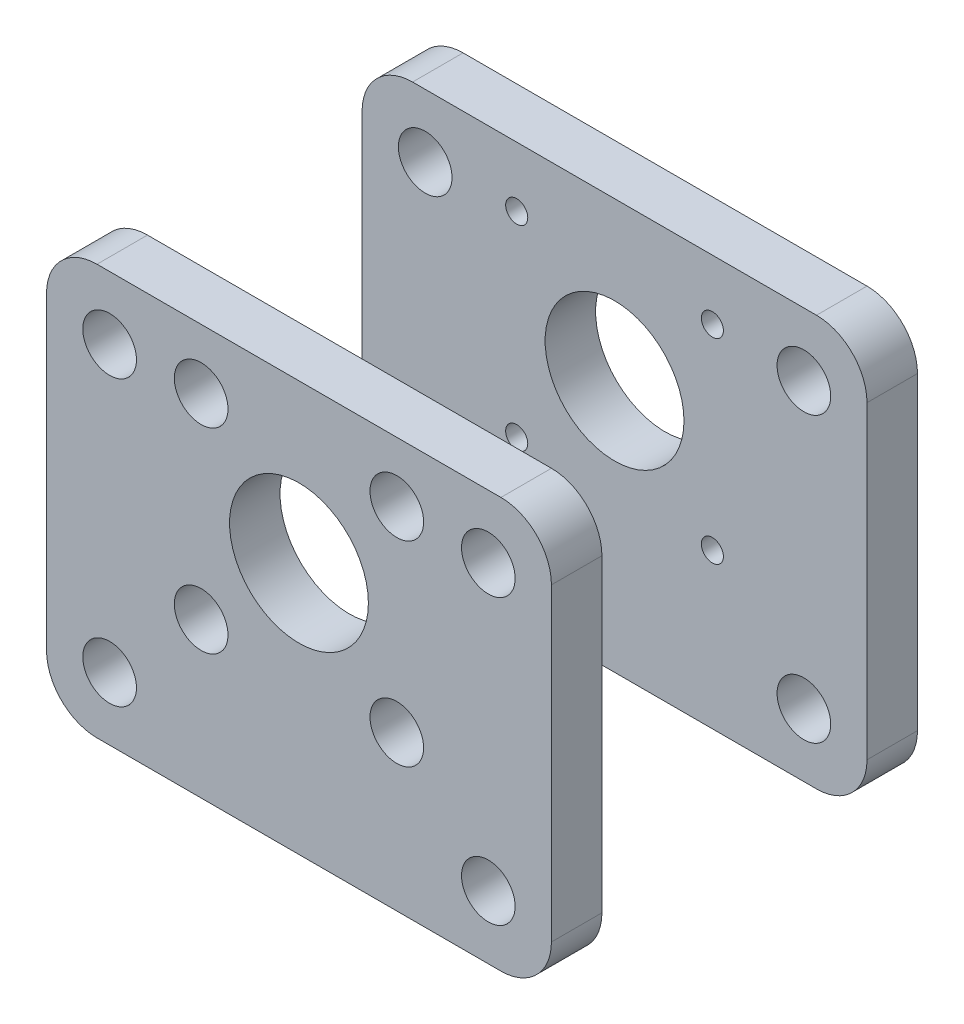
SolidWorks part; units mm, degrees
material "PET"
ref_plane "xy-antrieb" through (0, 0, 0) normal (0, 0, 1) x (1, 0, 0)
ref_plane "xz" through (0, 0, 0) normal (0, 1, 0) x (1, 0, 0)
ref_plane "yz" through (0, 0, 0) normal (1, 0, 0) x (0, 0, -1)
sketch "Skizze1" plane through (0, 0, 0) normal (0, 0, 1) x (1, 0, 0)
  line L1 (-40, 25) -> (40, 25)
  line L2 (-40, 25) -> (-40, -40)
  line L3 (-40, -40) -> (40, -40)
  line L4 (40, 25) -> (40, -40)
  line L5 (-15.5, 15.5) -> (15.5, 15.5) construction
  line L6 (-15.5, 15.5) -> (-15.5, -15.5) construction
  line L7 (-15.5, -15.5) -> (15.5, -15.5) construction
  line L8 (15.5, 15.5) -> (15.5, -15.5) construction
  line L9 (-30, 15) -> (30, 15) construction
  line L10 (-30, 15) -> (-30, -30) construction
  line L11 (-30, -30) -> (30, -30) construction
  line L12 (30, 15) -> (30, -30) construction
  circle A0 centre (0, 0) radius 11
  circle A1 centre (-15.5, 15.5) radius 1.75
  circle A2 centre (-15.5, -15.5) radius 1.75
  circle A3 centre (15.5, 15.5) radius 1.75
  circle A4 centre (15.5, -15.5) radius 1.75
  circle A5 centre (-30, 15) radius 10 construction
  circle A6 centre (-30, 15) radius 4.25
  circle A7 centre (30, 15) radius 4.25
  circle A8 centre (-30, -30) radius 4.25
  circle A9 centre (30, -30) radius 4.25
  point P4 (0, -40)
  point P12 (0, 15.5)
  point P13 (-15.5, 0)
  point P26 (0, -30)
  dimension "D1" = 22
  dimension "D3" = 3.5
  dimension "D4" = 10
  dimension "D5" = 8.5
  dimension "D6" = 80
  dimension "D8" = 10
  dimension "D2" = 31
  dimension "D7" = 30
  dimension "D9" = 65
extrude "Aufsatz-Linear austragen1" add sketch "Skizze1" along normal mid plane 8
ref_plane "xy-lager-mitte" through (0, 0, 50) normal (0, 0, 1) x (1, 0, 0)
sketch "Skizze2" plane through (0, 0, 50) normal (0, 0, 1) x (1, 0, 0)
  line L1 (-40, 25) -> (40, 25)
  line L2 (-40, 25) -> (-40, -40)
  line L3 (-40, -40) -> (40, -40)
  line L4 (40, 25) -> (40, -40)
  circle A0 centre (0, 0) radius 11
  circle A1 centre (-30, 15) radius 4.25 construction
  circle A2 centre (-30, 15) radius 4.25
  circle A3 centre (-30, -30) radius 4.25 construction
  circle A4 centre (-30, -30) radius 4.25
  circle A5 centre (30, -30) radius 4.25 construction
  circle A6 centre (30, -30) radius 4.25
  circle A7 centre (30, 15) radius 4.25 construction
  circle A8 centre (30, 15) radius 4.25
  circle A9 centre (-15.5, 15.5) radius 4.25
  circle A10 centre (-15.5, -15.5) radius 4.25
  circle A11 centre (15.5, -15.5) radius 4.25
  circle A12 centre (15.5, 15.5) radius 4.25
  dimension "D1" = 22
  dimension "D2" = 8.5
extrude "Aufsatz-Linear austragen2" add sketch "Skizze2" against normal mid plane 8 separate body
ref_plane "xy-mitte" through (0, 0, 25) normal (0, 0, 1) x (1, 0, 0)
fillet "Verrundung1" radius 8 4 edges at (40, -40, 0) (-40, -40, 0) (-40, 25, 0) (40, 25, 0)
fillet "Verrundung2" radius 8 4 edges at (40, -40, 50) (-40, -40, 50) (-40, 25, 50) (40, 25, 50)
